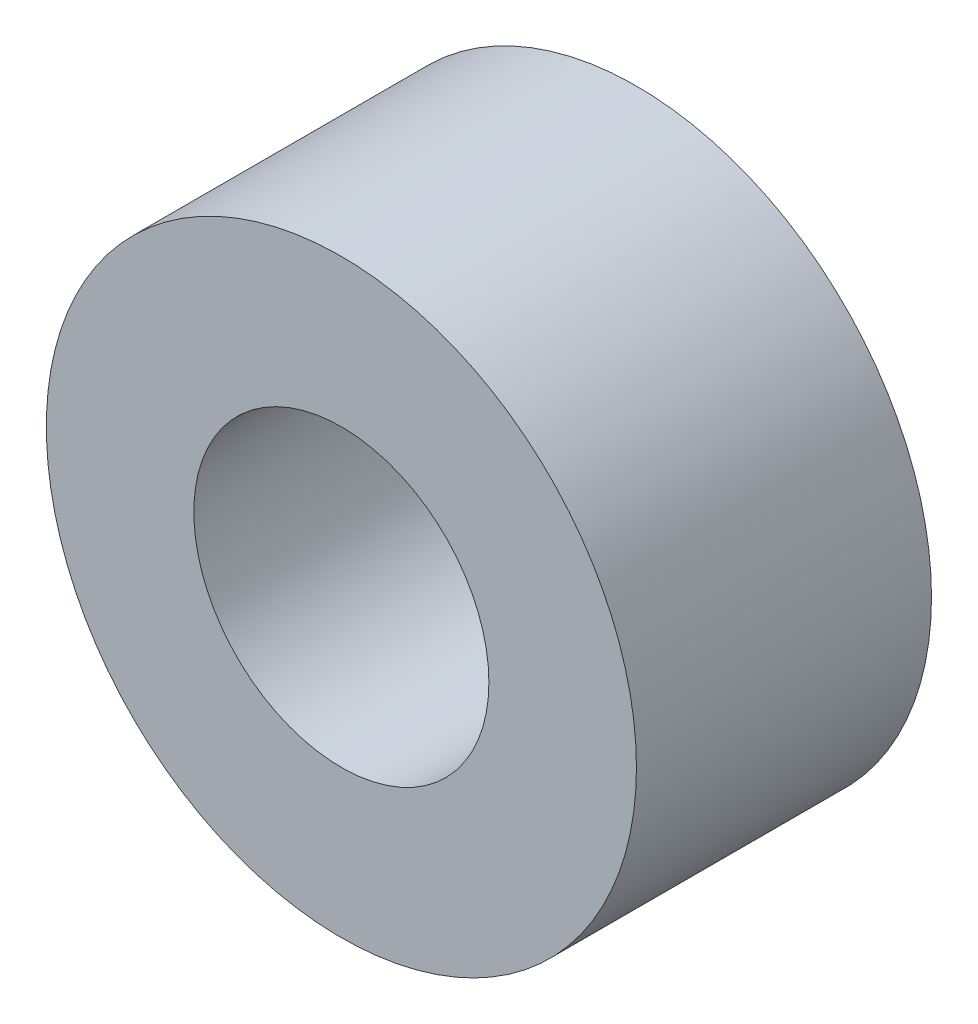
SolidWorks part; units mm, degrees
ref_plane "Front Plane" through (0, 0, 0) normal (0, 0, 1) x (1, 0, 0)
ref_plane "Top Plane" through (0, 0, 0) normal (0, 1, 0) x (1, 0, 0)
ref_plane "Right Plane" through (0, 0, 0) normal (1, 0, 0) x (0, 0, -1)
sketch "Sketch1" plane through (0, 0, 0) normal (0, 0, 1) x (1, 0, 0)
  circle A0 centre (0, 0) radius 25.4
  circle A1 centre (0, 0) radius 12.7
  dimension "D1" = 50.8
  dimension "D2" = 25.4
extrude "Boss-Extrude1" add sketch "Sketch1" along normal blind 25.4
